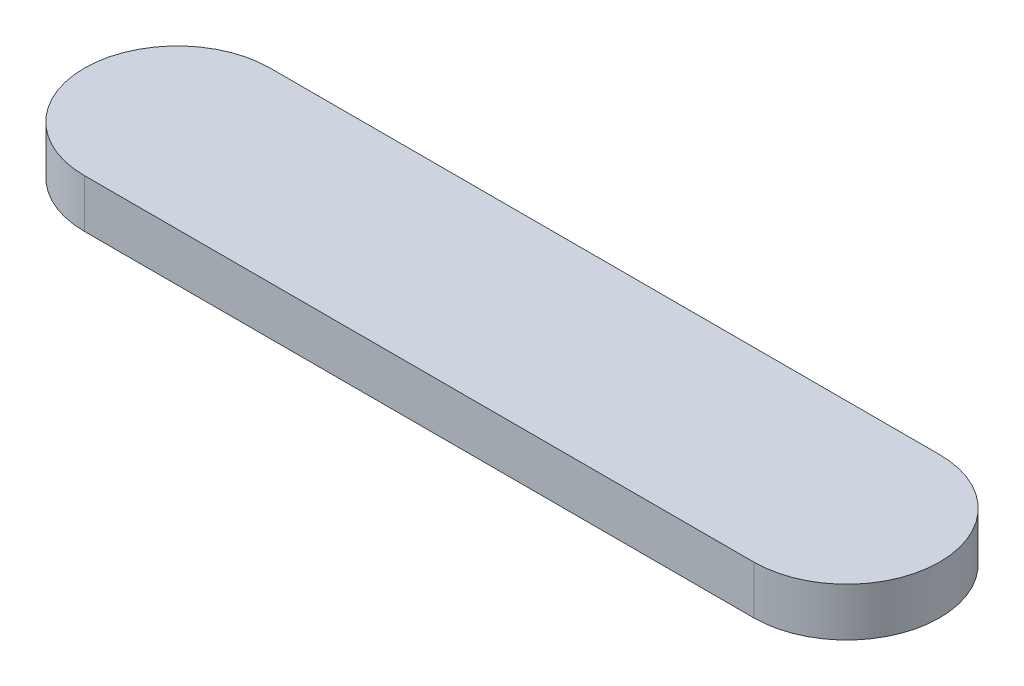
SolidWorks part; units mm, degrees
ref_plane "Front Plane" through (0, 0, 0) normal (0, 0, 1) x (1, 0, 0)
ref_plane "Top Plane" through (0, 0, 0) normal (0, 1, 0) x (1, 0, 0)
ref_plane "Right Plane" through (0, 0, 0) normal (1, 0, 0) x (0, 0, -1)
sketch "Sketch1" plane through (0, 0, 0) normal (0, 1, 0) x (1, 0, 0)
  line L0 (0, 0) -> (-50000, 0) construction
  line L1 (0, 0) -> (0, -50000) construction
  line L2 (0, 25) -> (180, 25)
  line L3 (0, -25) -> (180, -25)
  arc A0 (0, 25) -> (0, -25) centre (0, 0) ccw
  arc A1 (180, -25) -> (180, 25) centre (180, 0) ccw
  dimension "D1" = 180
  dimension "D2" = 25
extrude "Boss-Extrude1" add sketch "Sketch1" along normal blind 13
